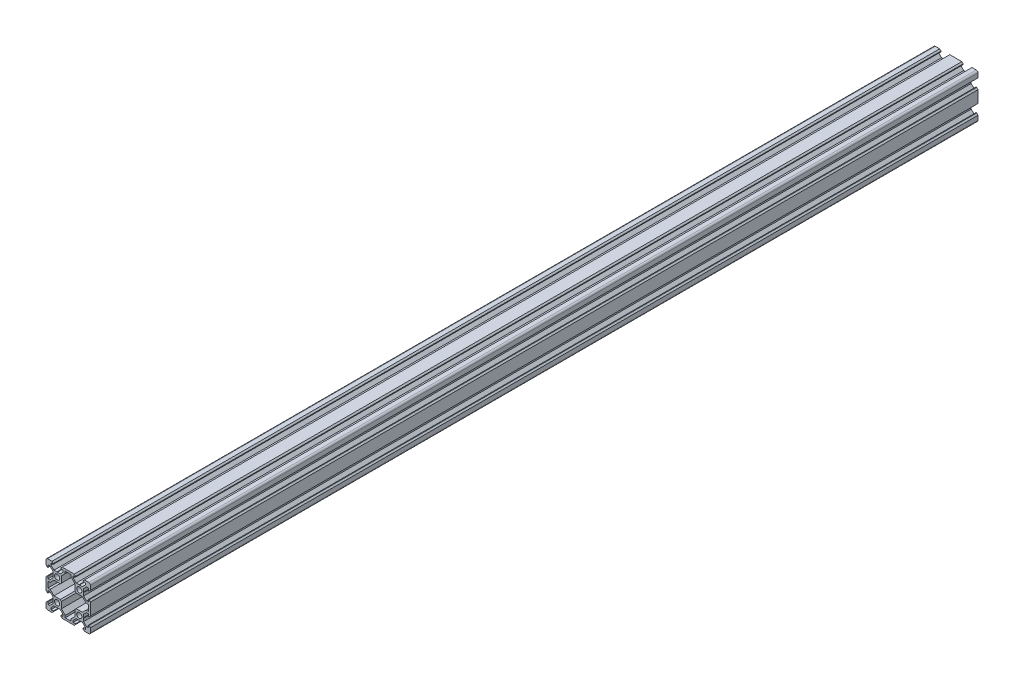
SolidWorks part; units mm, degrees
material "6061-T6 (SS)"
ref_plane "Front Plane" through (0, 0, 0) normal (0, 0, 1) x (1, 0, 0)
ref_plane "Top Plane" through (0, 0, 0) normal (0, 1, 0) x (1, 0, 0)
ref_plane "Right Plane" through (0, 0, 0) normal (1, 0, 0) x (0, 0, -1)
sketch "Sketch1" plane through (0, 0, 0) normal (0, 0, 1) x (1, 0, 0)
  line L1 (18.5, -20) -> (-18.5, -20)
  line L2 (20, -18.5) -> (20, 18.5)
  line L3 (18.5, 20) -> (-18.5, 20)
  line L4 (-20, -18.5) -> (-20, 18.5)
  line L5 (20, -20) -> (-20, 20) construction
  line L6 (20, 20) -> (-20, -20) construction
  circle A0 centre (-10, 10) radius 2.3
  circle A1 centre (10, -10) radius 2.3
  circle A2 centre (10, 10) radius 2.3
  circle A3 centre (-10, -10) radius 2.3
  arc A4 (-18.5, -20) -> (-20, -18.5) centre (-18.5, -18.5) cw
  arc A5 (18.5, -20) -> (20, -18.5) centre (18.5, -18.5) ccw
  arc A6 (20, 18.5) -> (18.5, 20) centre (18.5, 18.5) ccw
  arc A7 (-18.5, 20) -> (-20, 18.5) centre (-18.5, 18.5) ccw
  point P0 (0, 0)
  line B0 (-10, 10) -> (-10, 20) construction
  line B1 (-10, 13.69) -> (-10.21, 13.9)
  line B2 (-10.21, 13.9) -> (-12.8393, 13.9)
  line B3 (-12.8393, 13.9) -> (-15.5, 16.5607)
  line B4 (-15.5, 16.5607) -> (-15.5, 18.2)
  line B5 (-15.5, 18.2) -> (-13.395, 18.2)
  line B6 (-13.395, 18.2) -> (-13.395, 18.815)
  line B7 (-13.395, 18.815) -> (-14.58, 20)
  line B8 (-14.58, 20) -> (-5.42, 20)
  line B9 (-10, 10) -> (-15.9132, 15.9132) construction
  line B10 (-6.605, 18.815) -> (-5.42, 20)
  line B11 (-6.605, 18.2) -> (-6.605, 18.815)
  line B12 (-4.5, 18.2) -> (-6.605, 18.2)
  line B13 (-4.5, 16.5607) -> (-4.5, 18.2)
  line B14 (-7.1607, 13.9) -> (-4.5, 16.5607)
  line B15 (-9.79, 13.9) -> (-7.1607, 13.9)
  line B16 (-10, 13.69) -> (-9.79, 13.9)
  line B17 (10, 10) -> (10, 20) construction
  line B18 (10, 13.69) -> (9.79, 13.9)
  line B19 (9.79, 13.9) -> (7.1607, 13.9)
  line B20 (7.1607, 13.9) -> (4.5, 16.5607)
  line B21 (4.5, 16.5607) -> (4.5, 18.2)
  line B22 (4.5, 18.2) -> (6.605, 18.2)
  line B23 (6.605, 18.2) -> (6.605, 18.815)
  line B24 (6.605, 18.815) -> (5.42, 20)
  line B25 (5.42, 20) -> (14.58, 20)
  line B26 (10, 10) -> (4.0868, 15.9132) construction
  line B27 (13.395, 18.815) -> (14.58, 20)
  line B28 (13.395, 18.2) -> (13.395, 18.815)
  line B29 (15.5, 18.2) -> (13.395, 18.2)
  line B30 (15.5, 16.5607) -> (15.5, 18.2)
  line B31 (12.8393, 13.9) -> (15.5, 16.5607)
  line B32 (10.21, 13.9) -> (12.8393, 13.9)
  line B33 (10, 13.69) -> (10.21, 13.9)
  line B34 (-10, 10) -> (-20, 10) construction
  line B35 (-13.69, 10) -> (-13.9, 9.79)
  line B36 (-13.9, 9.79) -> (-13.9, 7.1607)
  line B37 (-13.9, 7.1607) -> (-16.5607, 4.5)
  line B38 (-16.5607, 4.5) -> (-18.2, 4.5)
  line B39 (-18.2, 4.5) -> (-18.2, 6.605)
  line B40 (-18.2, 6.605) -> (-18.815, 6.605)
  line B41 (-18.815, 6.605) -> (-20, 5.42)
  line B42 (-20, 5.42) -> (-20, 14.58)
  line B43 (-10, 10) -> (-15.9132, 4.0868) construction
  line B44 (-18.815, 13.395) -> (-20, 14.58)
  line B45 (-18.2, 13.395) -> (-18.815, 13.395)
  line B46 (-18.2, 15.5) -> (-18.2, 13.395)
  line B47 (-16.5607, 15.5) -> (-18.2, 15.5)
  line B48 (-13.9, 12.8393) -> (-16.5607, 15.5)
  line B49 (-13.9, 10.21) -> (-13.9, 12.8393)
  line B50 (-13.69, 10) -> (-13.9, 10.21)
  line B51 (-10, -10) -> (-20, -10) construction
  line B52 (-13.69, -10) -> (-13.9, -10.21)
  line B53 (-13.9, -10.21) -> (-13.9, -12.8393)
  line B54 (-13.9, -12.8393) -> (-16.5607, -15.5)
  line B55 (-16.5607, -15.5) -> (-18.2, -15.5)
  line B56 (-18.2, -15.5) -> (-18.2, -13.395)
  line B57 (-18.2, -13.395) -> (-18.815, -13.395)
  line B58 (-18.815, -13.395) -> (-20, -14.58)
  line B59 (-20, -14.58) -> (-20, -5.42)
  line B60 (-10, -10) -> (-15.9132, -15.9132) construction
  line B61 (-18.815, -6.605) -> (-20, -5.42)
  line B62 (-18.2, -6.605) -> (-18.815, -6.605)
  line B63 (-18.2, -4.5) -> (-18.2, -6.605)
  line B64 (-16.5607, -4.5) -> (-18.2, -4.5)
  line B65 (-13.9, -7.1607) -> (-16.5607, -4.5)
  line B66 (-13.9, -9.79) -> (-13.9, -7.1607)
  line B67 (-13.69, -10) -> (-13.9, -9.79)
  line B68 (-10, -10) -> (-10, -20) construction
  line B69 (-10, -13.69) -> (-9.79, -13.9)
  line B70 (-9.79, -13.9) -> (-7.1607, -13.9)
  line B71 (-7.1607, -13.9) -> (-4.5, -16.5607)
  line B72 (-4.5, -16.5607) -> (-4.5, -18.2)
  line B73 (-4.5, -18.2) -> (-6.605, -18.2)
  line B74 (-6.605, -18.2) -> (-6.605, -18.815)
  line B75 (-6.605, -18.815) -> (-5.42, -20)
  line B76 (-5.42, -20) -> (-14.58, -20)
  line B77 (-10, -10) -> (-4.0868, -15.9132) construction
  line B78 (-13.395, -18.815) -> (-14.58, -20)
  line B79 (-13.395, -18.2) -> (-13.395, -18.815)
  line B80 (-15.5, -18.2) -> (-13.395, -18.2)
  line B81 (-15.5, -16.5607) -> (-15.5, -18.2)
  line B82 (-12.8393, -13.9) -> (-15.5, -16.5607)
  line B83 (-10.21, -13.9) -> (-12.8393, -13.9)
  line B84 (-10, -13.69) -> (-10.21, -13.9)
  line B85 (10, -10) -> (10, -20) construction
  line B86 (10, -13.69) -> (10.21, -13.9)
  line B87 (10.21, -13.9) -> (12.8393, -13.9)
  line B88 (12.8393, -13.9) -> (15.5, -16.5607)
  line B89 (15.5, -16.5607) -> (15.5, -18.2)
  line B90 (15.5, -18.2) -> (13.395, -18.2)
  line B91 (13.395, -18.2) -> (13.395, -18.815)
  line B92 (13.395, -18.815) -> (14.58, -20)
  line B93 (14.58, -20) -> (5.42, -20)
  line B94 (10, -10) -> (15.9132, -15.9132) construction
  line B95 (6.605, -18.815) -> (5.42, -20)
  line B96 (6.605, -18.2) -> (6.605, -18.815)
  line B97 (4.5, -18.2) -> (6.605, -18.2)
  line B98 (4.5, -16.5607) -> (4.5, -18.2)
  line B99 (7.1607, -13.9) -> (4.5, -16.5607)
  line B100 (9.79, -13.9) -> (7.1607, -13.9)
  line B101 (10, -13.69) -> (9.79, -13.9)
  line B102 (10, 10) -> (20, 10) construction
  line B103 (13.69, 10) -> (13.9, 10.21)
  line B104 (13.9, 10.21) -> (13.9, 12.8393)
  line B105 (13.9, 12.8393) -> (16.5607, 15.5)
  line B106 (16.5607, 15.5) -> (18.2, 15.5)
  line B107 (18.2, 15.5) -> (18.2, 13.395)
  line B108 (18.2, 13.395) -> (18.815, 13.395)
  line B109 (18.815, 13.395) -> (20, 14.58)
  line B110 (20, 14.58) -> (20, 5.42)
  line B111 (10, 10) -> (15.9132, 15.9132) construction
  line B112 (18.815, 6.605) -> (20, 5.42)
  line B113 (18.2, 6.605) -> (18.815, 6.605)
  line B114 (18.2, 4.5) -> (18.2, 6.605)
  line B115 (16.5607, 4.5) -> (18.2, 4.5)
  line B116 (13.9, 7.1607) -> (16.5607, 4.5)
  line B117 (13.9, 9.79) -> (13.9, 7.1607)
  line B118 (13.69, 10) -> (13.9, 9.79)
  line B119 (10, -10) -> (20, -10) construction
  line B120 (13.69, -10) -> (13.9, -9.79)
  line B121 (13.9, -9.79) -> (13.9, -7.1607)
  line B122 (13.9, -7.1607) -> (16.5607, -4.5)
  line B123 (16.5607, -4.5) -> (18.2, -4.5)
  line B124 (18.2, -4.5) -> (18.2, -6.605)
  line B125 (18.2, -6.605) -> (18.815, -6.605)
  line B126 (18.815, -6.605) -> (20, -5.42)
  line B127 (20, -5.42) -> (20, -14.58)
  line B128 (10, -10) -> (15.9132, -4.0868) construction
  line B129 (18.815, -13.395) -> (20, -14.58)
  line B130 (18.2, -13.395) -> (18.815, -13.395)
  line B131 (18.2, -15.5) -> (18.2, -13.395)
  line B132 (16.5607, -15.5) -> (18.2, -15.5)
  line B133 (13.9, -12.8393) -> (16.5607, -15.5)
  line B134 (13.9, -10.21) -> (13.9, -12.8393)
  line B135 (13.69, -10) -> (13.9, -10.21)
  line B136 (-18.2, -2.7) -> (-18.2, 2.7)
  line B137 (-18.2, 2.7) -> (-16.2393, 2.7)
  line B138 (-16.2393, 2.7) -> (-12.8393, 6.1)
  line B139 (-12.8393, 6.1) -> (-7.1607, 6.1)
  line B140 (-10, 6.1) -> (-10, 0) construction
  line B141 (-10, 0) -> (-18.2, 0) construction
  line B142 (-12.8393, -6.1) -> (-7.1607, -6.1)
  line B143 (-16.2393, -2.7) -> (-12.8393, -6.1)
  line B144 (-18.2, -2.7) -> (-16.2393, -2.7)
  line B145 (-10, 6.1) -> (-10, 10) construction
  line B146 (-10, 10) -> (-15.0927, 4.9073) construction
  line B147 (-10, 10) -> (-6.3747, 6.3747) construction
  line B148 (2.7, 18.2) -> (2.7, 16.2393)
  line B149 (2.7, 16.2393) -> (6.1, 12.8393)
  line B150 (6.1, 12.8393) -> (6.1, 7.1607)
  line B151 (-6.1, 12.8393) -> (-6.1, 7.1607)
  line B152 (-2.7, 16.2393) -> (-6.1, 12.8393)
  line B153 (-2.7, 18.2) -> (-2.7, 16.2393)
  line B154 (2.7, 18.2) -> (-2.7, 18.2)
  line B155 (2.7, -18.2) -> (-2.7, -18.2)
  line B156 (-2.7, -18.2) -> (-2.7, -16.2393)
  line B157 (-2.7, -16.2393) -> (-6.1, -12.8393)
  line B158 (-6.1, -12.8393) -> (-6.1, -7.1607)
  line B159 (6.1, -12.8393) -> (6.1, -7.1607)
  line B160 (2.7, -16.2393) -> (6.1, -12.8393)
  line B161 (2.7, -18.2) -> (2.7, -16.2393)
  line B162 (0, 18.2) -> (0, -18.2) construction
  line B163 (12.8393, -6.1) -> (7.1607, -6.1)
  line B164 (16.2393, -2.7) -> (12.8393, -6.1)
  line B165 (18.2, -2.7) -> (16.2393, -2.7)
  line B166 (18.2, -2.7) -> (18.2, 2.7)
  line B167 (18.2, 2.7) -> (16.2393, 2.7)
  line B168 (16.2393, 2.7) -> (12.8393, 6.1)
  line B169 (12.8393, 6.1) -> (7.1607, 6.1)
  line B170 (-7.1607, 6.1) -> (-6.1, 7.1607)
  line B171 (6.1, 7.1607) -> (7.1607, 6.1)
  line B172 (7.1607, -6.1) -> (6.1, -7.1607)
  line B173 (-6.1, -7.1607) -> (-7.1607, -6.1)
  dimension "D4" = 4.6
  dimension "D5" = 1.5
  dimension "D1" = 40
  dimension "D2" = 10
  dimension "D3" = 10
sketch_block_instance "V Slot 2-1"
sketch_block "V Slot 2" parameters "D1"=10, "D2"=11, "D3"=4.3, "D4"=1.8, "D5"=0.21, "D6"=45, "D7"=9.16, "D8"=1.5, "D9"=6.79
sketch_block_instance "V Slot 2-2"
sketch_block_instance "V Slot 2-3"
sketch_block_instance "V Slot 2-4"
sketch_block_instance "V Slot 2-5"
sketch_block_instance "V Slot 2-6"
sketch_block_instance "V Slot 2-7"
sketch_block_instance "V Slot 2-8"
sketch_block_instance "Center Cutout 2-1"
sketch_block "Center Cutout 2" parameters "D1"=5.4, "D2"=12.2, "D3"=8.2, "D4"=45, "D5"=10, "D6"=1.5
extrude "Boss-Extrude1" add sketch "Sketch1" along normal blind 800 contours B135 B120 B121 B122 B123 B124 B125 B126 L2 B112 B113 B114 B115 B116 B117 B118 B103 B104 B105 B106 B107 B108 B109 A6 L3 B27 B28 B29 B30 B31 B32 B33 B18 B19 B20 B21 B22 B23 B24 B10 B11 B12 B13 B14 B15 B16 B1 B2 B3
